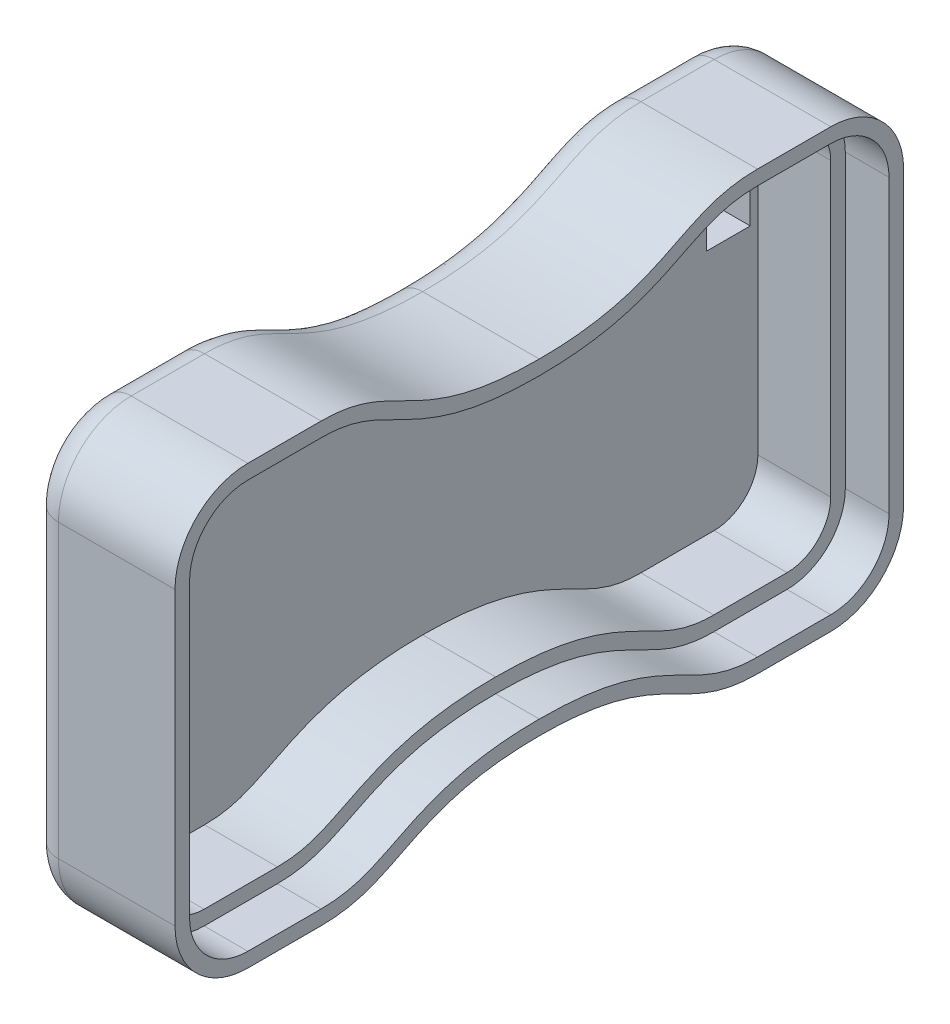
SolidWorks part; units mm, degrees
ref_plane "Front Plane" through (0, 0, 0) normal (0, 0, 1) x (1, 0, 0)
ref_plane "Top Plane" through (0, 0, 0) normal (0, 1, 0) x (1, 0, 0)
ref_plane "Right Plane" through (0, 0, 0) normal (1, 0, 0) x (0, 0, -1)
sketch "Sketch1" plane through (0, 0, 0) normal (1, 0, 0) x (0, 0, -1)
  line L0 (0, 15) -> (0, 0) construction
  line L1 (-20, 15) -> (20, 15)
  line L2 (-25, 10) -> (-25, -10)
  line L3 (-20, -15) -> (20, -15)
  line L4 (25, 10) -> (25, -10)
  line L5 (-25, 15) -> (25, -15) construction
  line L6 (-25, -15) -> (25, 15) construction
  line L7 (0, 0) -> (-25, 0) construction
  line L8 (-12.5513, 15) -> (-17.4047, 15) construction
  arc A0 (20, 15) -> (25, 10) centre (20, 10) cw
  arc A1 (20, -15) -> (25, -10) centre (20, -10) ccw
  arc A2 (-25, -10) -> (-20, -15) centre (-20, -10) ccw
  arc A3 (-20, 15) -> (-25, 10) centre (-20, 10) ccw
  spline S0 degree 3 poles (-14.9723, 15) (-9.5066, 15) (-8.8813, 11.1975) (0, 11.1975) knots 0 0 0 0 1 1 1 1
  spline S1 degree 3 poles (14.9723, 15) (9.5066, 15) (8.8813, 11.1975) (0, 11.1975) knots 0 0 0 0 1 1 1 1
  spline S2 degree 3 poles (14.9723, -15) (9.5066, -15) (8.8813, -11.1975) (0, -11.1975) knots 0 0 0 0 1 1 1 1
  spline S3 degree 3 poles (-14.9723, -15) (-9.5066, -15) (-8.8813, -11.1975) (0, -11.1975) knots 0 0 0 0 1 1 1 1
  point P0 (0, 0)
  dimension "D3" = 5
  dimension "D1" = 30
  dimension "D2" = 50
extrude "Boss-Extrude1" add sketch "Sketch1" along normal blind 10 and the other way blind 0.001 contours L3 S3 S2 A1 L4 A0 L1 S1 S0 A3 L2 A2
sketch "Sketch3" plane through (10, 0, 0) normal (1, 0, 0) x (0, 0, -1)
  line L0 (-14.9723, 13) -> (-20, 13)
  line L1 (-23, 10) -> (-23, -10)
  line L2 (-20, -13) -> (-14.9723, -13)
  line L3 (14.9723, -13) -> (20, -13)
  line L4 (23, -10) -> (23, 10)
  line L5 (20, 13) -> (14.9723, 13)
  line L6 (-20, -15) -> (-14.9723, -15)
  line L7 (14.9723, -15) -> (20, -15)
  line L8 (25, -10) -> (25, 10)
  line L9 (20, 15) -> (14.9723, 15)
  line L10 (-14.9723, 15) -> (-20, 15)
  line L11 (-25, 10) -> (-25, -10)
  line L12 (-20, -15) -> (-14.9723, -15)
  line L13 (14.9723, -15) -> (20, -15)
  line L14 (25, -10) -> (25, 10)
  line L15 (20, 15) -> (14.9723, 15)
  line L16 (-14.9723, 15) -> (-20, 15)
  line L17 (-25, 10) -> (-25, -10)
  arc A0 (-20, 13) -> (-23, 10) centre (-20, 10) ccw
  arc A1 (-23, -10) -> (-20, -13) centre (-20, -10) ccw
  arc A2 (20, -13) -> (23, -10) centre (20, -10) ccw
  arc A3 (23, 10) -> (20, 13) centre (20, 10) ccw
  arc A4 (20, -15) -> (25, -10) centre (20, -10) ccw
  arc A5 (25, 10) -> (20, 15) centre (20, 10) ccw
  arc A6 (-20, 15) -> (-25, 10) centre (-20, 10) ccw
  arc A7 (-25, -10) -> (-20, -15) centre (-20, -10) ccw
  arc A8 (20, -15) -> (25, -10) centre (20, -10) ccw
  arc A9 (25, 10) -> (20, 15) centre (20, 10) ccw
  arc A10 (-20, 15) -> (-25, 10) centre (-20, 10) ccw
  arc A11 (-25, -10) -> (-20, -15) centre (-20, -10) ccw
  spline S0 degree 1 poles (-14.9723, -13) (0, -9.1975) knots 0 0 1 1 construction
  spline S1 degree 1 poles (0, -9.1975) (14.9723, -13) knots 0 0 1 1 construction
  spline S2 degree 1 poles (14.9723, 13) (0, 9.1975) knots 0 0 1 1 construction
  spline S3 degree 1 poles (0, 9.1975) (-14.9723, 13) knots 0 0 1 1 construction
  spline S4 degree 3 poles (-3452.1362, 2030.6891) (3373.0771, -2044.0403) (-3427.9086, 1956.0226) (3537.6507, -1875.8244) knots -5.992003 -5.992003 -5.992003 -5.992003 6.796729 6.796729 6.796729 6.796729 only from (-14.9723, -15) to (0, -11.1975)
  spline S5 degree 3 poles (-3537.6755, -1875.8381) (3427.9208, 1956.0299) (-3373.0775, -2044.0407) (3452.1247, 2030.6823) knots -5.796744 -5.796744 -5.796744 -5.796744 6.991996 6.991996 6.991996 6.991996 only from (0, -11.1975) to (14.9723, -15)
  spline S6 degree 3 poles (3452.1362, -2030.6891) (-3373.0771, 2044.0403) (3427.9086, -1956.0226) (-3537.6507, 1875.8244) knots -5.992003 -5.992003 -5.992003 -5.992003 6.796729 6.796729 6.796729 6.796729 only from (14.9723, 15) to (0, 11.1975)
  spline S7 degree 3 poles (3537.6755, 1875.8381) (-3427.9208, -1956.0299) (3373.0775, 2044.0407) (-3452.1247, -2030.6823) knots -5.796744 -5.796744 -5.796744 -5.796744 6.991996 6.991996 6.991996 6.991996 only from (0, 11.1975) to (-14.9723, 15)
  spline S8 degree 3 poles (-14.9723, -15) (-9.5066, -15) (-8.8813, -11.1975) (0, -11.1975) knots 0 0 0 0 1 1 1 1
  spline S9 degree 3 poles (0, -11.1975) (8.8813, -11.1975) (9.5066, -15) (14.9723, -15) knots 0 0 0 0 1 1 1 1
  spline S10 degree 3 poles (14.9723, 15) (9.5066, 15) (8.8813, 11.1975) (0, 11.1975) knots 0 0 0 0 1 1 1 1
  spline S11 degree 3 poles (0, 11.1975) (-8.8813, 11.1975) (-9.5066, 15) (-14.9723, 15) knots 0 0 0 0 1 1 1 1
  spline S12 degree 3 poles (-14.9723, -13) (-14.7085, -13) (-14.156, -12.9755) (-13.2567, -12.8465) (-12.2691, -12.5617) (-11.0796, -12.027) (-9.6955, -11.3133) (-7.9992, -10.5262) (-6.2457, -9.9366) (-4.5982, -9.5711) (-3.2296, -9.3621) (-1.9626, -9.2513) (-0.8743, -9.2054) (-0.2879, -9.1975) (0, -9.1975) knots 0 0 0 0 0.0625 0.125 0.25 0.375 0.5 0.625 0.75 0.8125 0.875 0.9375 0.96875 1 1 1 1
  spline S13 degree 3 poles (0, -9.1975) (0.2879, -9.1975) (0.8743, -9.2054) (1.9626, -9.2513) (3.2296, -9.3621) (4.5982, -9.5711) (6.2457, -9.9366) (7.9992, -10.5262) (9.6955, -11.3133) (11.0796, -12.027) (12.2691, -12.5617) (13.2567, -12.8465) (14.156, -12.9755) (14.7085, -13) (14.9723, -13) knots 0 0 0 0 0.03125 0.0625 0.125 0.1875 0.25 0.375 0.5 0.625 0.75 0.875 0.9375 1 1 1 1
  spline S14 degree 3 poles (14.9723, 13) (14.7085, 13) (14.156, 12.9755) (13.2567, 12.8465) (12.2691, 12.5617) (11.0796, 12.027) (9.6955, 11.3133) (7.9992, 10.5262) (6.2457, 9.9366) (4.5982, 9.5711) (3.2296, 9.3621) (1.9626, 9.2513) (0.8743, 9.2054) (0.2879, 9.1975) (0, 9.1975) knots 0 0 0 0 0.0625 0.125 0.25 0.375 0.5 0.625 0.75 0.8125 0.875 0.9375 0.96875 1 1 1 1
  spline S15 degree 3 poles (0, 9.1975) (-0.2879, 9.1975) (-0.8743, 9.2054) (-1.9626, 9.2513) (-3.2296, 9.3621) (-4.5982, 9.5711) (-6.2457, 9.9366) (-7.9992, 10.5262) (-9.6955, 11.3133) (-11.0796, 12.027) (-12.2691, 12.5617) (-13.2567, 12.8465) (-14.156, 12.9755) (-14.7085, 13) (-14.9723, 13) knots 0 0 0 0 0.03125 0.0625 0.125 0.1875 0.25 0.375 0.5 0.625 0.75 0.875 0.9375 1 1 1 1
  dimension "D1" = 0
  dimension "D2" = 2
extrude "Cut-Extrude2" cut sketch "Sketch3" against normal blind 8 contours S14 S15 L0 A0 L1 A1 L2 S12 S13 L3 A2 L4 A3 L5
fillet "Fillet1" radius 2 14 edges at (-0.001, 15, 17.4862) (-0.001, 13.5355, 23.5355) (-0.001, 0, 25) (-0.001, -13.5355, 23.5355) (-0.001, -15, 17.4862) (-0.001, -15, -17.4862) (-0.001, -13.5355, -23.5355) (-0.001, 0, -25) (-0.001, 13.5355, -23.5355) (-0.001, 15, -17.4862)
sketch "Sketch4" plane through (-0.001, 0, 0) normal (-1, 0, 0) x (0, 0, 1)
  line L0 (-2.5669, 2.5526) -> (18.1435, 2.5526) construction
  line L2 (0, 0) -> (0, -9.1975) construction
  line L3 (1.2967, -1.9153) -> (-1.2967, -1.9153)
  line L4 (-1.2967, -1.9153) -> (-1.2967, -4.9809)
  line L5 (-1.2967, -4.9809) -> (-3.1856, -4.9809)
  line L6 (-3.1856, -4.9809) -> (0, -8.4801)
  line L7 (3.1856, -4.9809) -> (0, -8.4801)
  line L8 (1.2967, -4.9809) -> (3.1856, -4.9809)
  line L9 (1.2967, -1.9153) -> (1.2967, -4.9809)
  line L10 (-13, 7.5) -> (-13, -7.5) construction
  line L11 (-20.5, 0) -> (-5.5, 0) construction
  line L12 (-13, 0) -> (-20.0477, 2.5652) construction
  line L13 (-20.0477, 2.5652) -> (-5.9523, -2.5652) construction
  line L14 (-20.3897, 1.6255) -> (-6.2943, -3.5048) construction
  line L15 (-19.7057, 3.5048) -> (-5.6103, -1.6255) construction
  line L16 (-16, 7.9926) -> (-16, -7.9198) construction
  line L17 (-10, 7.9926) -> (-10, -7.9198) construction
  line L18 (-20, -13) -> (-14.9723, -13) construction
  line L19 (-23, 10) -> (-23, -10) construction
  line L20 (-17, 7.9926) -> (-17, -7.9198) construction
  line L21 (-11, 7.9926) -> (-11, -7.9198) construction
  line L22 (-15, 7.9926) -> (-15, -7.9198) construction
  line L23 (-9, 7.9926) -> (-9, -7.9198) construction
  line L24 (-13, 3) -> (-5.1002, 3) construction
  line L25 (-13, -3) -> (-22.0111, -3) construction
  circle A0 centre (-13, 0) radius 7.5 construction
  circle A1 centre (-13, 0) radius 5.5 construction
  text T0 "BEAST \r\n    pro" font "Century Gothic" height in points 22
  point P17 (0, -1.9153)
  dimension "D1" = 20
  dimension "D5" = 15
  dimension "D6" = 11
  dimension "D2" = 1
  dimension "D4" = 3
  dimension "D7" = 13
  dimension "D8" = 10
  dimension "D9" = 1
  dimension "D11" = 3
  dimension "D12" = 3
  dimension "D3" = 1
  dimension "D10" = 1
extrude "Cut-Extrude3" cut sketch "Sketch4" against normal blind 1
sketch "Sketch5" plane through (-0.001, 0, 0) normal (-1, 0, 0) x (0, 0, 1)
  line L0 (-13, -3) -> (-22.0111, -3) construction
  line L1 (-20.3897, 1.6255) -> (-6.2943, -3.5048) construction
  line L2 (-15, 7.9926) -> (-15, -7.9198) construction
  line L3 (-19.7057, 3.5048) -> (-5.6103, -1.6255) construction
  line L4 (-13, 3) -> (-5.1002, 3) construction
  line L5 (-9, 7.9926) -> (-9, -7.9198) construction
  line L6 (-11, 7.9926) -> (-11, -7.9198) construction
  line L7 (-17, 7.9926) -> (-17, -7.9198) construction
  line L8 (-13, -3) -> (-22.0111, -3)
  line L9 (-20.3897, 1.6255) -> (-6.2943, -3.5048)
  line L10 (-15, 7.9926) -> (-15, -7.9198)
  line L11 (-19.7057, 3.5048) -> (-5.6103, -1.6255)
  line L12 (-13, 3) -> (-5.1002, 3)
  line L13 (-9, 7.9926) -> (-9, -7.9198)
  line L14 (-11, 7.9926) -> (-11, -7.9198)
  line L15 (-17, 7.9926) -> (-17, -7.9198)
  circle A0 centre (-13, 0) radius 5.5 construction
  circle A1 centre (-13, 0) radius 7.5 construction
  circle A2 centre (-13, 0) radius 5.5
  circle A3 centre (-13, 0) radius 7.5
  point P0 (-15, 7.9926)
extrude "Cut-Extrude4" cut sketch "Sketch5" against normal blind 1 contours L15 A3 L11 A2 | L14 A3 L10 A2 | L12 A3 L13 A2 | L11 A3 L9 A2 | L11 A2 L9 L15 | L14 L11 L10 L9 | L9 A2 L11 L13 | L9 A3 L11 A2 | L13 A3 L9 A2 | L10 A3 L14 A2 | L8 A3 L15 A2
sketch "Sketch6" plane through (-0.001, 0, 0) normal (-1, 0, 0) x (0, 0, 1)
  line L0 (-25, -10) -> (-25, 10) construction
  line L1 (-20, 15) -> (-14.9723, 15) construction
  circle A0 centre (-20, 7) radius 1.5
  dimension "D1" = 5
  dimension "D2" = 3
  dimension "D3" = 8
extrude "Cut-Extrude5" [suppressed] cut sketch "Sketch6" against normal blind 5
sketch "Sketch7" plane through (10, 0, 0) normal (1, 0, 0) x (0, 0, -1)
  line L0 (-14.9723, 13) -> (-20, 13) construction
  line L1 (-14.9723, 13) -> (-20, 13)
  line L2 (20, 13) -> (14.9723, 13) construction
  line L3 (23, -10) -> (23, 10) construction
  line L4 (14.9723, -13) -> (20, -13) construction
  line L5 (-20, -13) -> (-14.9723, -13) construction
  line L6 (-23, 10) -> (-23, -10) construction
  line L7 (20, 13) -> (14.9723, 13)
  line L8 (23, -10) -> (23, 10)
  line L9 (14.9723, -13) -> (20, -13)
  line L10 (-20, -13) -> (-14.9723, -13)
  line L11 (-23, 10) -> (-23, -10)
  line L12 (-14.9723, 14) -> (-20, 14)
  line L13 (-24, 10) -> (-24, -10)
  line L14 (-20, -14) -> (-14.9723, -14)
  line L15 (14.9723, -14) -> (20, -14)
  line L16 (24, -10) -> (24, 10)
  line L17 (20, 14) -> (14.9723, 14)
  arc A0 (23, 10) -> (20, 13) centre (20, 10) ccw construction
  arc A1 (20, -13) -> (23, -10) centre (20, -10) ccw construction
  arc A2 (-23, -10) -> (-20, -13) centre (-20, -10) ccw construction
  arc A3 (-20, 13) -> (-23, 10) centre (-20, 10) ccw construction
  arc A4 (23, 10) -> (20, 13) centre (20, 10) ccw
  arc A5 (20, -13) -> (23, -10) centre (20, -10) ccw
  arc A6 (-23, -10) -> (-20, -13) centre (-20, -10) ccw
  arc A7 (-20, 13) -> (-23, 10) centre (-20, 10) ccw
  arc A8 (-20, 14) -> (-24, 10) centre (-20, 10) ccw
  arc A9 (-24, -10) -> (-20, -14) centre (-20, -10) ccw
  arc A10 (20, -14) -> (24, -10) centre (20, -10) ccw
  arc A11 (24, 10) -> (20, 14) centre (20, 10) ccw
  spline S0 degree 3 poles (-1977.8297, -155.9738) (70.9149, 0.0854) (22.5233, 14.1752) (13.2567, 12.8465) (12.2691, 12.5617) (11.0796, 12.027) (9.6955, 11.3133) (7.9992, 10.5262) (6.2457, 9.9366) (4.5982, 9.5711) (3.2296, 9.3621) (1.9626, 9.2513) (-12.7913, 8.6293) (-55.8151, 18.2835) (1999.1695, 63.6121) knots -2.326169 -2.326169 -2.326169 -2.326169 0.0625 0.125 0.25 0.375 0.5 0.625 0.75 0.8125 0.875 0.9375 0.96875 2.569657 2.569657 2.569657 2.569657 only from (14.9723, 13) to (0, 9.1975) construction
  spline S1 degree 3 poles (1999.1672, -63.612) (-55.815, -18.2835) (-12.7913, -8.6293) (1.9626, -9.2513) (3.2296, -9.3621) (4.5982, -9.5711) (6.2457, -9.9366) (7.9992, -10.5262) (9.6955, -11.3133) (11.0796, -12.027) (12.2691, -12.5617) (13.2567, -12.8465) (22.5233, -14.1752) (70.9143, -0.0856) (-1977.7865, 155.9705) knots -1.569656 -1.569656 -1.569656 -1.569656 0.03125 0.0625 0.125 0.1875 0.25 0.375 0.5 0.625 0.75 0.875 0.9375 3.326152 3.326152 3.326152 3.326152 only from (0, -9.1975) to (14.9723, -13) construction
  spline S2 degree 3 poles (1977.8297, 155.9738) (-70.9149, -0.0854) (-22.5233, -14.1752) (-13.2567, -12.8465) (-12.2691, -12.5617) (-11.0796, -12.027) (-9.6955, -11.3133) (-7.9992, -10.5262) (-6.2457, -9.9366) (-4.5982, -9.5711) (-3.2296, -9.3621) (-1.9626, -9.2513) (12.7913, -8.6293) (55.8151, -18.2835) (-1999.1695, -63.6121) knots -2.326169 -2.326169 -2.326169 -2.326169 0.0625 0.125 0.25 0.375 0.5 0.625 0.75 0.8125 0.875 0.9375 0.96875 2.569657 2.569657 2.569657 2.569657 only from (-14.9723, -13) to (0, -9.1975) construction
  spline S3 degree 3 poles (-1999.1672, 63.612) (55.815, 18.2835) (12.7913, 8.6293) (-1.9626, 9.2513) (-3.2296, 9.3621) (-4.5982, 9.5711) (-6.2457, 9.9366) (-7.9992, 10.5262) (-9.6955, 11.3133) (-11.0796, 12.027) (-12.2691, 12.5617) (-13.2567, 12.8465) (-22.5233, 14.1752) (-70.9143, 0.0856) (1977.7865, -155.9705) knots -1.569656 -1.569656 -1.569656 -1.569656 0.03125 0.0625 0.125 0.1875 0.25 0.375 0.5 0.625 0.75 0.875 0.9375 3.326152 3.326152 3.326152 3.326152 only from (0, 9.1975) to (-14.9723, 13) construction
  spline S4 degree 3 poles (14.9723, 13) (14.7085, 13) (14.156, 12.9755) (13.2567, 12.8465) (12.2691, 12.5617) (11.0796, 12.027) (9.6955, 11.3133) (7.9992, 10.5262) (6.2457, 9.9366) (4.5982, 9.5711) (3.2296, 9.3621) (1.9626, 9.2513) (0.8743, 9.2054) (0.2879, 9.1975) (0, 9.1975) knots 0 0 0 0 0.0625 0.125 0.25 0.375 0.5 0.625 0.75 0.8125 0.875 0.9375 0.96875 1 1 1 1
  spline S5 degree 3 poles (0, -9.1975) (0.2879, -9.1975) (0.8743, -9.2054) (1.9626, -9.2513) (3.2296, -9.3621) (4.5982, -9.5711) (6.2457, -9.9366) (7.9992, -10.5262) (9.6955, -11.3133) (11.0796, -12.027) (12.2691, -12.5617) (13.2567, -12.8465) (14.156, -12.9755) (14.7085, -13) (14.9723, -13) knots 0 0 0 0 0.03125 0.0625 0.125 0.1875 0.25 0.375 0.5 0.625 0.75 0.875 0.9375 1 1 1 1
  spline S6 degree 3 poles (-14.9723, -13) (-14.7085, -13) (-14.156, -12.9755) (-13.2567, -12.8465) (-12.2691, -12.5617) (-11.0796, -12.027) (-9.6955, -11.3133) (-7.9992, -10.5262) (-6.2457, -9.9366) (-4.5982, -9.5711) (-3.2296, -9.3621) (-1.9626, -9.2513) (-0.8743, -9.2054) (-0.2879, -9.1975) (0, -9.1975) knots 0 0 0 0 0.0625 0.125 0.25 0.375 0.5 0.625 0.75 0.8125 0.875 0.9375 0.96875 1 1 1 1
  spline S7 degree 3 poles (0, 9.1975) (-0.2879, 9.1975) (-0.8743, 9.2054) (-1.9626, 9.2513) (-3.2296, 9.3621) (-4.5982, 9.5711) (-6.2457, 9.9366) (-7.9992, 10.5262) (-9.6955, 11.3133) (-11.0796, 12.027) (-12.2691, 12.5617) (-13.2567, 12.8465) (-14.156, 12.9755) (-14.7085, 13) (-14.9723, 13) knots 0 0 0 0 0.03125 0.0625 0.125 0.1875 0.25 0.375 0.5 0.625 0.75 0.875 0.9375 1 1 1 1
  spline S8 degree 1 poles (-14.9723, -14) (0, -10.1975) knots 0 0 1 1 construction
  spline S9 degree 1 poles (0, -10.1975) (14.9723, -14) knots 0 0 1 1 construction
  spline S10 degree 1 poles (14.9723, 14) (0, 10.1975) knots 0 0 1 1 construction
  spline S11 degree 1 poles (0, 10.1975) (-14.9723, 14) knots 0 0 1 1 construction
  spline S12 degree 3 poles (-14.9723, -14) (-14.679, -14) (-14.0705, -13.9733) (-13.2942, -13.8627) (-12.5898, -13.6962) (-11.695, -13.4017) (-10.6277, -12.9192) (-9.245, -12.2062) (-7.6254, -11.456) (-5.9752, -10.9012) (-4.4159, -10.5551) (-3.1129, -10.356) (-1.8963, -10.2494) (-0.8476, -10.2052) (-0.2789, -10.1975) (0, -10.1975) knots 0 0 0 0 0.0625 0.125 0.1875 0.25 0.375 0.5 0.625 0.75 0.8125 0.875 0.9375 0.96875 1 1 1 1
  spline S13 degree 3 poles (0, -10.1975) (0.2789, -10.1975) (0.8476, -10.2052) (1.8963, -10.2494) (3.1129, -10.356) (4.4159, -10.5551) (5.9752, -10.9012) (7.6254, -11.456) (9.245, -12.2062) (10.6277, -12.9192) (11.695, -13.4017) (12.5898, -13.6962) (13.2942, -13.8627) (14.0705, -13.9733) (14.679, -14) (14.9723, -14) knots 0 0 0 0 0.03125 0.0625 0.125 0.1875 0.25 0.375 0.5 0.625 0.75 0.8125 0.875 0.9375 1 1 1 1
  spline S14 degree 3 poles (14.9723, 14) (14.679, 14) (14.0705, 13.9733) (13.2942, 13.8627) (12.5898, 13.6962) (11.695, 13.4017) (10.6277, 12.9192) (9.245, 12.2062) (7.6254, 11.456) (5.9752, 10.9012) (4.4159, 10.5551) (3.1129, 10.356) (1.8963, 10.2494) (0.8476, 10.2052) (0.2789, 10.1975) (0, 10.1975) knots 0 0 0 0 0.0625 0.125 0.1875 0.25 0.375 0.5 0.625 0.75 0.8125 0.875 0.9375 0.96875 1 1 1 1
  spline S15 degree 3 poles (0, 10.1975) (-0.2789, 10.1975) (-0.8476, 10.2052) (-1.8963, 10.2494) (-3.1129, 10.356) (-4.4159, 10.5551) (-5.9752, 10.9012) (-7.6254, 11.456) (-9.245, 12.2062) (-10.6277, 12.9192) (-11.695, 13.4017) (-12.5898, 13.6962) (-13.2942, 13.8627) (-14.0705, 13.9733) (-14.679, 14) (-14.9723, 14) knots 0 0 0 0 0.03125 0.0625 0.125 0.1875 0.25 0.375 0.5 0.625 0.75 0.8125 0.875 0.9375 1 1 1 1
  dimension "D1" = 1
extrude "Cut-Extrude6" cut sketch "Sketch7" against normal blind 3
sketch "Sketch9" plane through (2, 0, 0) normal (1, 0, 0) x (0, 0, -1)
  line L1 (22.476, 6.869) -> (19.476, 6.869)
  line L2 (22.476, 6.869) -> (22.476, 3.869)
  line L3 (22.476, 3.869) -> (19.476, 3.869)
  line L4 (19.476, 6.869) -> (19.476, 3.869)
  dimension "D1" = 3
extrude "Cut-Extrude7" cut sketch "Sketch9" against normal mid plane 5
